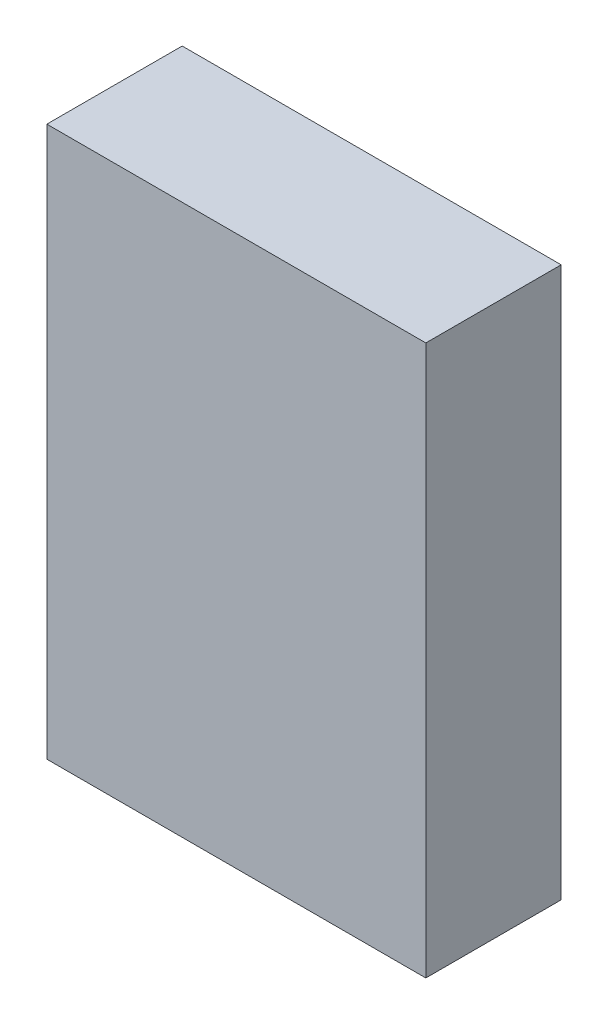
SolidWorks part; units mm, degrees
ref_plane "Plan de face" through (0, 0, 0) normal (0, 0, 1) x (1, 0, 0)
ref_plane "Plan de dessus" through (0, 0, 0) normal (0, 1, 0) x (1, 0, 0)
ref_plane "Plan de droite" through (0, 0, 0) normal (1, 0, 0) x (0, 0, -1)
sketch "Esquisse1" plane through (0, 0, 0) normal (0, 0, 1) x (1, 0, 0)
  line L0 (-1.3, 2.0635) -> (1.5, 2.0635)
  line L1 (1.5, 2.0635) -> (1.5, -2)
  line L2 (1.5, -2) -> (-1.3, -2)
  line L3 (-1.3, -2) -> (-1.3, 2.0635)
extrude "Component_Outline" add sketch "Esquisse1" along normal blind 1 separate body
sketch3d "Esquisse3D1"
  line L0 (0, 0, 0) -> (1, 0, 0)
  line L1 (0, 0, 0) -> (0, 1, 0)
  line L2 (0, 0, 0) -> (0, 0, 1)
  point P0 (0, 0, 0)
